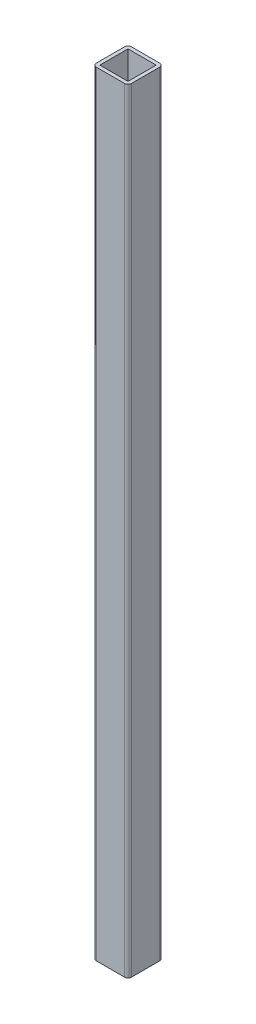
SolidWorks part; units mm, degrees
ref_plane "Front Plane" through (0, 0, 0) normal (0, 0, 1) x (1, 0, 0)
ref_plane "Top Plane" through (0, 0, 0) normal (0, 1, 0) x (1, 0, 0)
ref_plane "Right Plane" through (0, 0, 0) normal (1, 0, 0) x (0, 0, -1)
sketch "Sketch4" plane through (0, 0, 0) normal (0, 1, 0) x (1, 0, 0)
  line L0 (10.16, 10.16) -> (10.16, -10.16)
  line L1 (12.7, 12.7) -> (-12.7, 12.7)
  line L2 (12.7, 12.7) -> (12.7, -12.7)
  line L3 (12.7, -12.7) -> (-12.7, -12.7)
  line L4 (-12.7, 12.7) -> (-12.7, -12.7)
  line L5 (10.16, -10.16) -> (-10.16, -10.16)
  line L6 (-10.16, 10.16) -> (-10.16, -10.16)
  line L7 (10.16, 10.16) -> (-10.16, 10.16)
  point P0 (0, 0)
  dimension "D1" = 25.4
  dimension "D2" = 25.4
  dimension "D3" = 2.54
extrude "Boss-Extrude6" add sketch "Sketch4" along normal blind 558.8 contours L4 L3 L2 L1
shell "Shell1" thickness 2.54
fillet "Fillet1" radius 2.54 4 edges at (-12.7, 279.4, 12.7) (12.7, 279.4, 12.7) (12.7, 279.4, -12.7) (-12.7, 279.4, -12.7)
